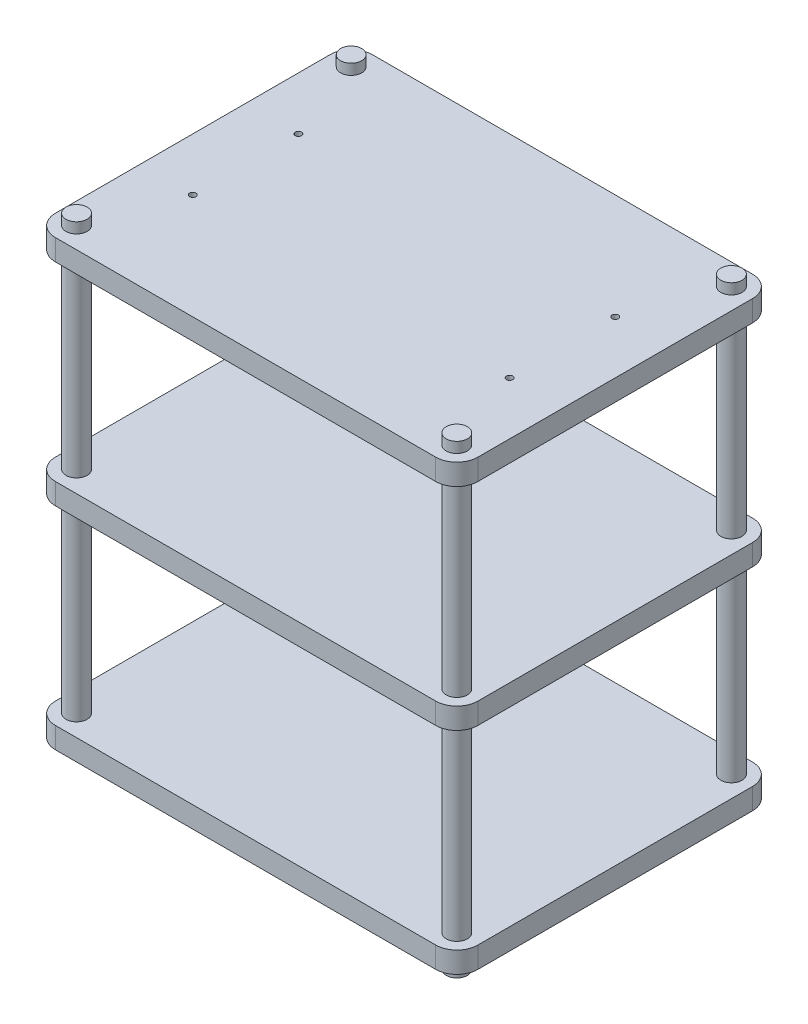
SolidWorks part; units mm, degrees
ref_plane "Front Plane" through (0, 0, 0) normal (0, 0, 1) x (1, 0, 0)
ref_plane "Top Plane" through (0, 0, 0) normal (0, 1, 0) x (1, 0, 0)
ref_plane "Right Plane" through (0, 0, 0) normal (1, 0, 0) x (0, 0, -1)
sketch "Sketch1" plane through (0, 0, 0) normal (0, 1, 0) x (1, 0, 0)
  line L1 (-100, 75) -> (100, 75)
  line L2 (-100, 75) -> (-100, -75)
  line L3 (-100, -75) -> (100, -75)
  line L4 (100, 75) -> (100, -75)
  line L5 (-100, 75) -> (100, -75) construction
  line L6 (-100, -75) -> (100, 75) construction
  point P0 (0, 0)
  dimension "D1" = 200
  dimension "D2" = 150
extrude "Boss-Extrude1" add sketch "Sketch1" along normal blind 10
sketch "Sketch2" plane through (0, 10, 0) normal (0, 1, 0) x (1, 0, 0)
  line L0 (-100, 75) -> (-100, -75) construction
  line L1 (100, 75) -> (-100, 75) construction
  line L2 (0, 73.0671) -> (0, 83.6614) construction
  line L3 (0, 83.6614) -> (0, -94.4748) construction
  line L4 (-110.8687, 0) -> (113.9791, 0) construction
  circle A0 centre (-90, 65) radius 5
  circle A1 centre (90, 65) radius 5
  circle A2 centre (90, -65) radius 5
  circle A3 centre (-90, -65) radius 5
  dimension "D1" = 10
  dimension "D2" = 10
  dimension "D3" = 10
extrude "Cut-Extrude1" cut sketch "Sketch2" against normal blind 10
ref_plane "Plane1" through (0, 100, 0) normal (0, 1, 0) x (1, 0, 0)
sketch "Sketch3" plane through (0, 100, 0) normal (0, 1, 0) x (1, 0, 0)
  line L1 (-100, 75) -> (100, 75)
  line L2 (-100, 75) -> (-100, -75)
  line L3 (-100, -75) -> (100, -75)
  line L4 (100, 75) -> (100, -75)
  line L5 (-100, 75) -> (100, -75) construction
  line L6 (-100, -75) -> (100, 75) construction
  circle A0 centre (-90, 65) radius 5
  circle A1 centre (90, 65) radius 5
  circle A2 centre (-90, -65) radius 5
  circle A3 centre (90, -65) radius 5
  point P0 (0, 0)
extrude "Boss-Extrude2" add sketch "Sketch3" along normal blind 10 separate body
ref_plane "Plane4" through (0, 200, 0) normal (0, 1, 0) x (1, 0, 0)
sketch "Sketch4" plane through (0, 200, 0) normal (0, 1, 0) x (1, 0, 0)
  line L1 (-100, 75) -> (100, 75)
  line L2 (-100, 75) -> (-100, -75)
  line L3 (-100, -75) -> (100, -75)
  line L4 (100, 75) -> (100, -75)
  line L5 (-100, 75) -> (100, -75) construction
  line L6 (-100, -75) -> (100, 75) construction
  circle A0 centre (-90, 65) radius 5
  circle A1 centre (90, 65) radius 5
  circle A2 centre (90, -65) radius 5
  circle A3 centre (-90, -65) radius 5
  point P1 (0, 0)
extrude "Boss-Extrude3" add sketch "Sketch4" along normal blind 10 separate body
sketch "Sketch5" plane through (0, 210, 0) normal (0, 1, 0) x (1, 0, 0)
  circle A0 centre (-90, -65) radius 5
sketch "Sketch17" plane through (0, 200, 0) normal (0, -1, 0) x (1, 0, 0)
  circle A0 centre (-90, -65) radius 5.3637
sketch "Sketch21" plane through (0, 10, 0) normal (0, 1, 0) x (1, 0, 0)
  circle A0 centre (-90, -65) radius 5
  circle A1 centre (-90, 65) radius 5
  circle A2 centre (90, 65) radius 5
  circle A3 centre (90, -65) radius 5
  dimension "D1" = 10
  dimension "D2" = 10
  dimension "D3" = 10
  dimension "D4" = 10
extrude "Boss-Extrude13" add sketch "Sketch21" along normal blind 205
sketch "Sketch22" plane through (0, 10, 0) normal (0, 1, 0) x (1, 0, 0)
  circle A0 centre (-90, 65) radius 5
  circle A1 centre (-90, -65) radius 5
  circle A2 centre (90, -65) radius 5
  circle A3 centre (90, 65) radius 5
  dimension "D1" = 10
  dimension "D2" = 10
  dimension "D3" = 10
  dimension "D4" = 10
extrude "Boss-Extrude14" add sketch "Sketch22" against normal blind 15
fillet "Fillet2" radius 10 12 edges at (-100, 205, 75) (-100, 105, 75) (-100, 5, -75) (100, 5, -75) (100, 105, -75) (100, 205, -75) (100, 205, 75) (100, 105, 75) (-100, 205, -75) (-100, 105, -75) (-100, 5, 75) (100, 5, 75)
sketch "Sketch23" plane through (0, 210, 0) normal (0, 1, 0) x (1, 0, 0)
  line L0 (-100, 65) -> (-100, -65) construction
  line L1 (-140.155, 0) -> (119.4256, 0) construction
  line L2 (0, -82.5) -> (0, 82.5) construction
  circle A0 centre (-75, 25) radius 1.5
  circle A1 centre (-75, -25) radius 1.5
  circle A2 centre (75, -25) radius 1.5
  circle A3 centre (75, 25) radius 1.5
  dimension "D1" = 3
  dimension "D2" = 25
  dimension "D3" = 25
extrude "Cut-Extrude2" cut sketch "Sketch23" against normal blind 10
sketch "Sketch30" plane through (0, 200, 0) normal (0, -1, 0) x (-1, 0, 0)
  line L1 (33, -23.5) -> (-33, -23.5)
  line L2 (33, -23.5) -> (33, 23.5)
  line L3 (33, 23.5) -> (-33, 23.5)
  line L4 (-33, -23.5) -> (-33, 23.5)
  line L5 (33, -23.5) -> (-33, 23.5) construction
  line L6 (33, 23.5) -> (-33, -23.5) construction
  point P0 (0, 0)
  dimension "D1" = 47
  dimension "D2" = 66
extrude "Boss-Extrude16" add sketch "Sketch30" along normal blind 1
